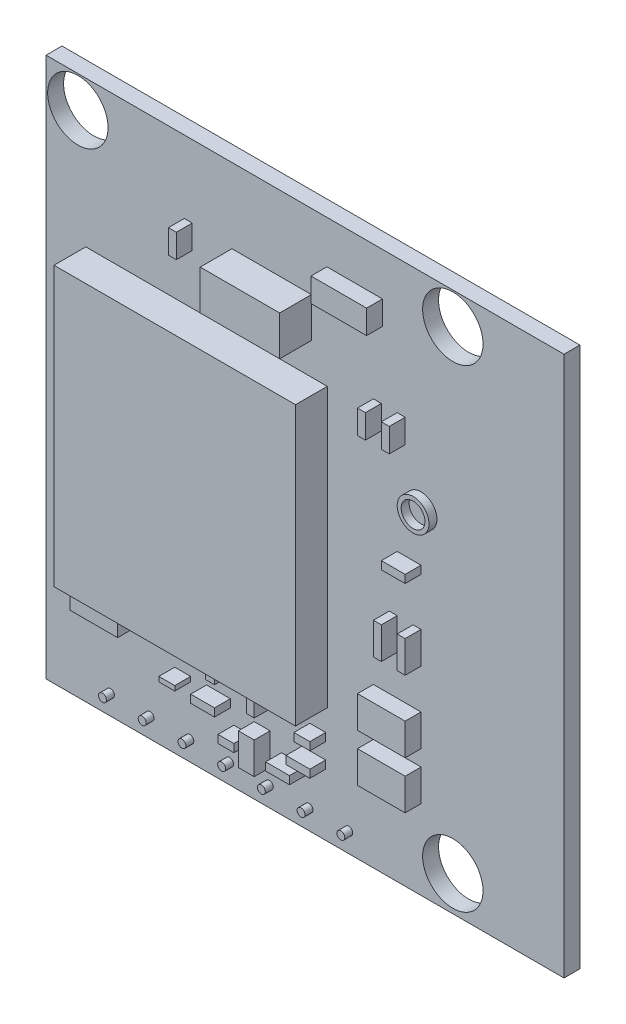
SolidWorks part; units mm, degrees
ref_plane "Plan de face" through (0, 0, 0) normal (0, 0, 1) x (1, 0, 0)
ref_plane "Plan de dessus" through (0, 0, 0) normal (0, 1, 0) x (1, 0, 0)
ref_plane "Plan de droite" through (0, 0, 0) normal (1, 0, 0) x (0, 0, -1)
sketch "Esquisse1" plane through (0, 0, 0) normal (0, 0, 1) x (1, 0, 0)
  line L1 (0, 0) -> (-32.6, 0)
  line L2 (0, 0) -> (0, 34)
  line L3 (0, 34) -> (-32.6, 34)
  line L4 (-32.6, 0) -> (-32.6, 34)
  dimension "D1" = 32.6
  dimension "D2" = 34
extrude "Boss.-Extru.1" add sketch "Esquisse1" along normal blind 1
sketch "Esquisse2" plane through (0, 0, 1) normal (0, 0, 1) x (1, 0, 0)
  line L0 (0, 34) -> (-32.6, 34) construction
  line L1 (-20.9, 29.3) -> (-15.9, 29.3)
  line L2 (-20.9, 29.3) -> (-20.9, 26.8)
  line L3 (-20.9, 26.8) -> (-15.9, 26.8)
  line L4 (-15.9, 29.3) -> (-15.9, 26.8)
  line L5 (-30.1, 24.8) -> (-14.9, 24.8)
  line L6 (-30.1, 24.8) -> (-30.1, 7.28)
  line L7 (-30.1, 7.28) -> (-14.9, 7.28)
  line L8 (-14.9, 24.8) -> (-14.9, 7.28)
  line L9 (-30.1, 6.5) -> (-27.1, 6.5)
  line L10 (-30.1, 6.5) -> (-30.1, 5.5)
  line L11 (-30.1, 5.5) -> (-27.1, 5.5)
  line L12 (-27.1, 6.5) -> (-27.1, 5.5)
  line L13 (-12, 10) -> (-9, 10)
  line L14 (-12, 10) -> (-12, 8)
  line L15 (-12, 8) -> (-9, 8)
  line L16 (-9, 10) -> (-9, 8)
  line L17 (-12, 7) -> (-9, 7)
  line L18 (-12, 7) -> (-12, 5)
  line L19 (-12, 5) -> (-9, 5)
  line L20 (-9, 7) -> (-9, 5)
  line L21 (-32.6, 0) -> (0, 0) construction
  line L22 (-32.6, 34) -> (-32.6, 0) construction
  line L23 (0, 0) -> (0, 34) construction
  dimension "D1" = 17.52
  dimension "D2" = 15.2
  dimension "D3" = 9.2
  dimension "D4" = 1
  dimension "D5" = 3
  dimension "D6" = 5.5
  dimension "D7" = 0
  dimension "D8" = 2.5
  dimension "D9" = 1
  dimension "D10" = 2.5
  dimension "D11" = 5
  dimension "D12" = 2
  dimension "D13" = 3
  dimension "D14" = 3
  dimension "D15" = 2
  dimension "D16" = 2
  dimension "D17" = 1
  dimension "D18" = 5
  dimension "D19" = 9
extrude "Boss.-Extru.2" add sketch "Esquisse2" along normal blind 1
sketch "Esquisse3" plane through (0, 0, 2) normal (0, 0, 1) x (1, 0, 0)
  line L0 (-14.9, 7.28) -> (-14.9, 24.8) construction
  line L1 (-30.1, 7.28) -> (-14.9, 7.28)
  line L2 (-30.1, 7.28) -> (-30.1, 24.8)
  line L3 (-30.1, 24.8) -> (-14.9, 24.8)
  line L4 (-14.9, 7.28) -> (-14.9, 24.8)
  line L5 (-14.9, 24.8) -> (-30.1, 24.8) construction
  line L7 (-20.9, 29.3) -> (-15.9, 29.3)
  line L8 (-20.9, 29.3) -> (-20.9, 26.8)
  line L9 (-20.9, 26.8) -> (-15.9, 26.8)
  line L10 (-15.9, 29.3) -> (-15.9, 26.8)
extrude "Boss.-Extru.3" add sketch "Esquisse3" along normal blind 1
sketch "Esquisse4" plane through (0, 0, 1) normal (0, 0, 1) x (1, 0, 0)
  line L0 (-9, 10) -> (-12, 10) construction
  line L1 (-9, 12.5) -> (-9.5, 12.5)
  line L2 (-9, 12.5) -> (-9, 14.5)
  line L3 (-9, 14.5) -> (-9.5, 14.5)
  line L4 (-9.5, 12.5) -> (-9.5, 14.5)
  line L5 (-10.5, 12.5) -> (-11, 12.5)
  line L6 (-10.5, 12.5) -> (-10.5, 14.5)
  line L7 (-10.5, 14.5) -> (-11, 14.5)
  line L8 (-11, 12.5) -> (-11, 14.5)
  line L9 (-9, 17.5) -> (-10.5, 17.5)
  line L10 (-9, 17.5) -> (-9, 18)
  line L11 (-9, 18) -> (-10.5, 18)
  line L12 (-10.5, 17.5) -> (-10.5, 18)
  line L13 (-10, 24.0663) -> (-10.5, 24.0663)
  line L14 (-10, 24.0663) -> (-10, 25.5663)
  line L15 (-10, 25.5663) -> (-10.5, 25.5663)
  line L16 (-10.5, 24.0663) -> (-10.5, 25.5663)
  line L17 (-11.5, 24.0663) -> (-12, 24.0663)
  line L18 (-11.5, 24.0663) -> (-11.5, 25.5663)
  line L19 (-11.5, 25.5663) -> (-12, 25.5663)
  line L20 (-12, 24.0663) -> (-12, 25.5663)
  line L21 (-11.4271, 29.8) -> (-14.9271, 29.8)
  line L22 (-11.4271, 29.8) -> (-11.4271, 31.3)
  line L23 (-11.4271, 31.3) -> (-14.9271, 31.3)
  line L24 (-14.9271, 29.8) -> (-14.9271, 31.3)
  line L25 (-23.4, 27.9494) -> (-23.9, 27.9494)
  line L26 (-23.4, 27.9494) -> (-23.4, 29.4494)
  line L27 (-23.4, 29.4494) -> (-23.9, 29.4494)
  line L28 (-23.9, 27.9494) -> (-23.9, 29.4494)
  line L29 (-15, 5.8833) -> (-16, 5.8833)
  line L30 (-15, 5.8833) -> (-15, 5.3833)
  line L31 (-15, 5.3833) -> (-16, 5.3833)
  line L32 (-16, 5.8833) -> (-16, 5.3833)
  line L33 (-15, 4.3833) -> (-16.5, 4.3833)
  line L34 (-15, 4.3833) -> (-15, 3.8833)
  line L35 (-15, 3.8833) -> (-16.5, 3.8833)
  line L36 (-16.5, 4.3833) -> (-16.5, 3.8833)
  line L37 (-18.5, 2.222) -> (-19.5, 2.222)
  line L38 (-18.5, 2.222) -> (-18.5, 4.222)
  line L39 (-18.5, 4.222) -> (-19.5, 4.222)
  line L40 (-19.5, 2.222) -> (-19.5, 4.222)
  line L41 (-18.5, 5.4185) -> (-19, 5.4185)
  line L42 (-18.5, 5.4185) -> (-18.5, 6.4185)
  line L43 (-18.5, 6.4185) -> (-19, 6.4185)
  line L44 (-19, 5.4185) -> (-19, 6.4185)
  line L45 (-16.2802, 2.89) -> (-17.7802, 2.89)
  line L46 (-16.2802, 2.89) -> (-16.2802, 3.39)
  line L47 (-16.2802, 3.39) -> (-17.7802, 3.39)
  line L48 (-17.7802, 2.89) -> (-17.7802, 3.39)
  line L49 (-19.7802, 2.89) -> (-20.7802, 2.89)
  line L50 (-19.7802, 2.89) -> (-19.7802, 3.39)
  line L51 (-19.7802, 3.39) -> (-20.7802, 3.39)
  line L52 (-20.7802, 2.89) -> (-20.7802, 3.39)
  line L53 (-21, 4.222) -> (-22.5, 4.222)
  line L54 (-21, 4.222) -> (-21, 4.722)
  line L55 (-21, 4.722) -> (-22.5, 4.722)
  line L56 (-22.5, 4.222) -> (-22.5, 4.722)
  line L57 (-23.5, 4.39) -> (-24.5, 4.39)
  line L58 (-23.5, 4.39) -> (-23.5, 4.69)
  line L59 (-23.5, 4.69) -> (-24.5, 4.69)
  line L60 (-24.5, 4.39) -> (-24.5, 4.69)
  line L61 (-21, 5.9829) -> (-21.5531, 5.9829)
  line L62 (-21, 5.9829) -> (-21, 6.8182)
  line L63 (-21, 6.8182) -> (-21.5531, 6.8182)
  line L64 (-21.5531, 5.9829) -> (-21.5531, 6.8182)
  line L65 (-9, 10) -> (-12, 10) construction
  line L66 (-9, 8) -> (-9, 10) construction
  line L67 (-15.9, 29.3) -> (-20.9, 29.3) construction
  line L68 (-20.9, 29.3) -> (-20.9, 26.8) construction
  line L69 (0, 0) -> (0, 34) construction
  dimension "D1" = 0.5
  dimension "D2" = 0.5
  dimension "D3" = 2
  dimension "D4" = 2
  dimension "D5" = 2.5
  dimension "D6" = 2.5
  dimension "D7" = 0
  dimension "D8" = 1
  dimension "D9" = 1.5
  dimension "D10" = 0.5
  dimension "D11" = 0
  dimension "D12" = 3
  dimension "D13" = 1.5
  dimension "D14" = 1.5
  dimension "D15" = 0.5
  dimension "D16" = 0.5
  dimension "D17" = 1.5
  dimension "D18" = 3.5
  dimension "D19" = 1.5
  dimension "D20" = 0.5
  dimension "D21" = 0.5
  dimension "D22" = 2.5
  dimension "D23" = 1.5
  dimension "D24" = 0.5
  dimension "D25" = 0.5
  dimension "D26" = 1
  dimension "D27" = 1
  dimension "D28" = 1
  dimension "D29" = 0.5
  dimension "D30" = 1
  dimension "D31" = 2
  dimension "D32" = 0.5
  dimension "D33" = 0.5
  dimension "D34" = 0.5
  dimension "D35" = 0.3
  dimension "D36" = 1
  dimension "D37" = 1
  dimension "D38" = 1.5
  dimension "D39" = 1.5
  dimension "D40" = 1
  dimension "D41" = 1
  dimension "D42" = 2
  dimension "D43" = 0
  dimension "D44" = 2
  dimension "D45" = 0
  dimension "D46" = 2
  dimension "D47" = 0
  dimension "D48" = 15
  dimension "D49" = 1
  dimension "D50" = 10
extrude "Boss.-Extru.4" add sketch "Esquisse4" along normal blind 1
sketch "Esquisse5" plane through (0, 0, 1) normal (0, 0, 1) x (1, 0, 0)
  line L0 (0, 0) -> (0, 34) construction
  line L1 (0, 34) -> (-32.6, 34) construction
  circle A0 centre (-9, 21) radius 1
  circle A1 centre (-9, 21) radius 0.75
  dimension "D1" = 2
  dimension "D4" = 1.5
  dimension "D2" = 9
  dimension "D3" = 13
extrude "Boss.-Extru.5" add sketch "Esquisse5" along normal blind 0.5
sketch "Esquisse6" plane through (0, 0, 1) normal (0, 0, 1) x (1, 0, 0)
  line L0 (-32.6, 34) -> (-28.6, 30) construction
  line L1 (-32.6, 34) -> (-28.6, 34)
  line L2 (-32.6, 34) -> (-32.6, 30)
  line L3 (-32.6, 30) -> (-28.6, 30)
  line L4 (-28.6, 34) -> (-28.6, 30)
  line L5 (0, 0) -> (0, 34) construction
  line L6 (-32.6, 0) -> (0, 0) construction
  circle A0 centre (-30.6, 32) radius 1.9
  circle A1 centre (-7, 32) radius 1.9
  circle A2 centre (-7, 2.2) radius 1.9
  point P15 (-5.9704, 0.6058)
  dimension "D3" = 3.8
  dimension "D5" = 3.8
  dimension "D6" = 3.8
  dimension "D1" = 4
  dimension "D2" = 4
  dimension "D4" = 7
  dimension "D7" = 7
  dimension "D8" = 2.2
extrude "Enlèv. mat.-Extru.1" cut sketch "Esquisse6" against normal blind 8.5 contours A2 | A1 | A0
sketch "Esquisse7" plane through (0, 0, 0) normal (0, 0, -1) x (-1, 0, 0)
  line L0 (32.6, 0) -> (0, 0) construction
  line L1 (12, 0) -> (30.1, 0)
  line L2 (12, 0) -> (12, 2.5)
  line L3 (12, 2.5) -> (30.1, 2.5)
  line L4 (30.1, 0) -> (30.1, 2.5)
  line L5 (32.6, 34) -> (32.6, 0) construction
  dimension "D1" = 2.5
  dimension "D2" = 2.5
  dimension "D3" = 18.1
extrude "Boss.-Extru.6" add sketch "Esquisse7" along normal blind 2.5
sketch "Esquisse8" plane through (0, 0, -2.5) normal (0, 0, -1) x (-1, 0, 0)
  line L0 (12, 1.25) -> (13.55, 1.25) construction
  line L1 (12, 2.5) -> (12, 0) construction
  line L2 (13.55, 1.25) -> (22.1749, 1.25) construction
  line L3 (22.1749, 1.25) -> (30.1, 1.25) construction
  line L4 (30.1, 0) -> (30.1, 2.5) construction
  circle A0 centre (13.55, 1.25) radius 0.25
  circle A1 centre (16.05, 1.25) radius 0.25
  circle A2 centre (18.55, 1.25) radius 0.25
  circle A3 centre (21.05, 1.25) radius 0.25
  circle A4 centre (23.55, 1.25) radius 0.25
  circle A5 centre (26.05, 1.25) radius 0.25
  circle A6 centre (28.55, 1.25) radius 0.25
  dimension "D2" = 0.5
  dimension "D1" = 1.55
  dimension "D3" = 7
extrude "Boss.-Extru.7" add sketch "Esquisse8" along normal blind 5 and the other way blind 4
